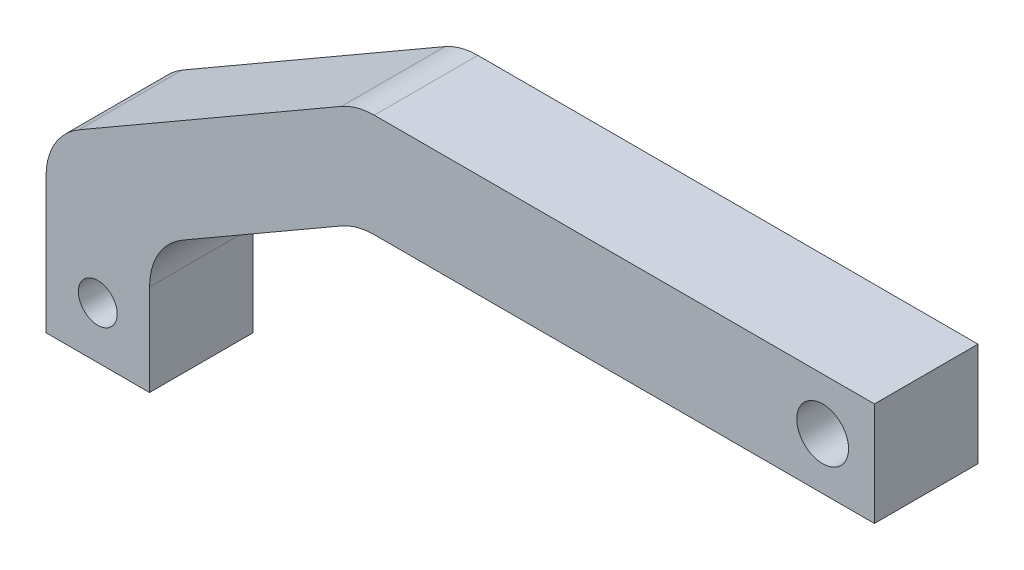
SolidWorks part; units mm, degrees
ref_plane "Front Plane" through (0, 0, 0) normal (0, 0, 1) x (1, 0, 0)
ref_plane "Top Plane" through (0, 0, 0) normal (0, 1, 0) x (1, 0, 0)
ref_plane "Right Plane" through (0, 0, 0) normal (1, 0, 0) x (0, 0, -1)
sketch "Sketch1" plane through (0, 0, 0) normal (0, 0, 1) x (1, 0, 0)
  line L0 (10, 0) -> (10, 25)
  line L1 (10, 25) -> (50, 48.094)
  line L2 (50, 48.094) -> (150, 48.094)
  line L3 (150, 48.094) -> (150, 68.094)
  line L4 (150, 68.094) -> (50, 68.094)
  line L5 (50, 68.094) -> (-10, 33.453)
  line L6 (-10, 33.453) -> (-10, 0)
  line L7 (-10, 0) -> (10, 0)
  dimension "D1" = 20
  dimension "D2" = 10
  dimension "D4" = 25
  dimension "D5" = 120
  dimension "D6" = 40
  dimension "D7" = 100
  dimension "D8" = 20
extrude "Boss-Extrude1" add sketch "Sketch1" along normal blind 20
fillet "Fillet2" radius 12.7 4 edges at (50, 68.094, 10) (-10, 33.453, 10) (50, 48.094, 10) (10, 25, 10)
sketch "Sketch2" plane through (0, 0, 20) normal (0, 0, 1) x (1, 0, 0)
  line L0 (53.403, 48.094) -> (150, 48.094) construction
  line L1 (150, 48.094) -> (150, 68.094) construction
  line L2 (-10, 0) -> (10, 0) construction
  line L3 (10, 0) -> (10, 17.6677) construction
  circle A0 centre (140, 58.094) radius 5
  circle A1 centre (0, 10) radius 3.75
  dimension "D1" = 10
  dimension "D4" = 7.5
  dimension "D2" = 10
  dimension "D3" = 10
  dimension "D5" = 10
  dimension "D6" = 10
extrude "Cut-Extrude1" cut sketch "Sketch2" against normal through all
